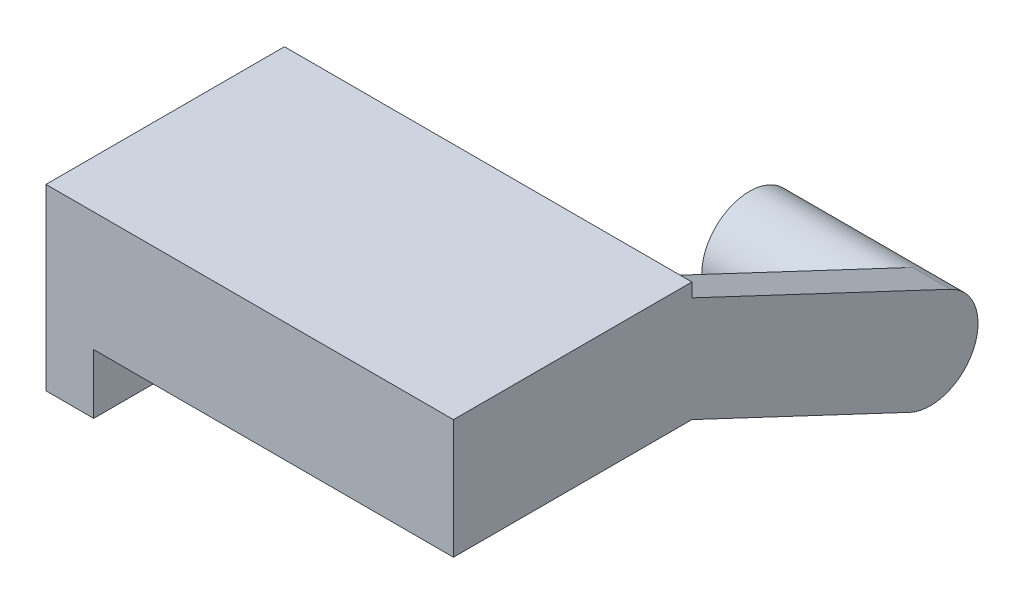
SolidWorks part; units mm, degrees
material "ABS"
ref_plane "Front Plane" through (0, 0, 0) normal (0, 0, 1) x (1, 0, 0)
ref_plane "Top Plane" through (0, 0, 0) normal (0, 1, 0) x (1, 0, 0)
ref_plane "Right Plane" through (0, 0, 0) normal (1, 0, 0) x (0, 0, -1)
sketch "Sketch1" plane through (0, 0, 0) normal (1, 0, 0) x (0, 0, -1)
  line L0 (-5, -5) -> (5, -5) construction
  line L1 (-10, -7.5) -> (10, -7.5)
  line L2 (-10, -7.5) -> (-10, 7.5)
  line L3 (-10, 7.5) -> (10, 7.5)
  line L4 (10, -7.5) -> (10, 7.5)
  line L5 (-10, -7.5) -> (10, 7.5) construction
  line L6 (-10, 7.5) -> (10, -7.5) construction
  circle A0 centre (-5, -5) radius 1.35
  circle A1 centre (5, -5) radius 1.35
  point P0 (0, 0)
  dimension "D1" = 2.7
  dimension "D2" = 10
  dimension "D3" = 20
  dimension "D4" = 15
  dimension "D5" = 2.5
extrude "Boss-Extrude1" add sketch "Sketch1" along normal blind 4
sketch "Sketch2" plane through (4, 0, 0) normal (1, 0, 0) x (0, 0, -1)
  line L0 (-10, -7.5) -> (10, -7.5) construction
  line L1 (10, -7.5) -> (10, 7.5) construction
  line L2 (-10, 7.5) -> (10, 7.5)
  line L3 (-10, 7.5) -> (-10, -2.5)
  line L4 (-10, -2.5) -> (10, -2.5)
  line L13 (10, 7.5) -> (10, -2.5)
  dimension "D1" = 5
extrude "Boss-Extrude2" add sketch "Sketch2" along normal blind 27
sketch "Sketch3" plane through (31, 0, 0) normal (1, 0, 0) x (0, 0, -1)
  line L1 (-10, 7.5) -> (34, 7.5) construction
  line L2 (-10, 7.5) -> (-10, -11.5) construction
  line L3 (-10, -11.5) -> (34, -11.5) construction
  line L4 (34, 7.5) -> (34, -11.5) construction
  line L5 (-10, 7.5) -> (10, 7.5)
  line L6 (-10, 7.5) -> (-10, -2.5)
  line L7 (-10, -2.5) -> (10, -2.5)
  line L8 (10, 7.5) -> (10, -2.5)
  line L10 (10, 1.9216) -> (30, -7.5) construction
  line L13 (-10, -2.5) -> (10, -2.5) construction
  line L14 (11.7046, 5.5402) -> (31.7046, -3.8814)
  line L15 (8.2954, -1.697) -> (28.2954, -11.1186)
  line L16 (11.7046, 5.5402) -> (10, 6.3432)
  arc A2 (11.7046, 5.5402) -> (8.2954, -1.697) centre (10, 1.9216) ccw
  arc A3 (28.2954, -11.1186) -> (31.7046, -3.8814) centre (30, -7.5) ccw
  point P8 (20, -2.7892)
  dimension "D3" = 4
  dimension "D1" = 19
  dimension "D2" = 44
extrude "Boss-Extrude3" add sketch "Sketch3" along normal blind 3.175
sketch "Sketch4" plane through (31, 0, 0) normal (-1, 0, 0) x (0, 0, 1)
  circle A0 centre (-30, -7.5) radius 4
  dimension "D2" = 8
extrude "Boss-Extrude4" add sketch "Sketch4" along normal blind 12
